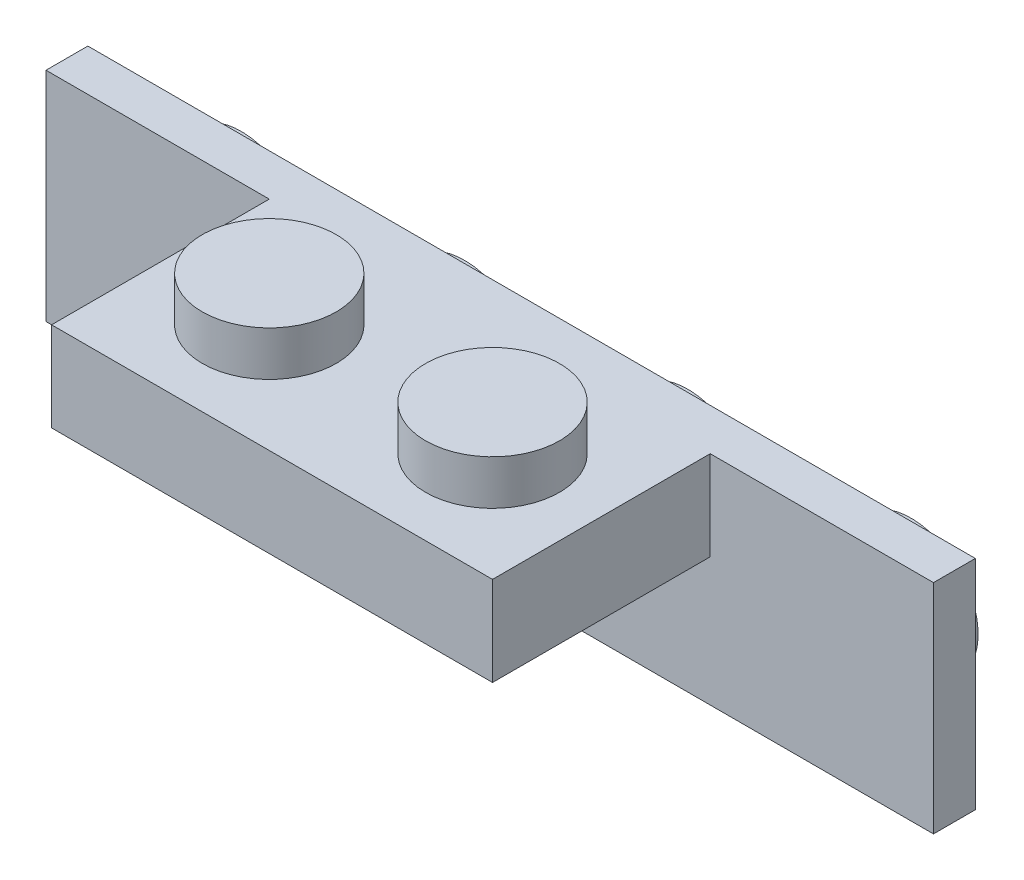
SolidWorks part; units mm, degrees
material "ABS"
ref_plane "Front Plane" through (0, 0, 0) normal (0, 0, 1) x (1, 0, 0)
ref_plane "Top Plane" through (0, 0, 0) normal (0, 1, 0) x (1, 0, 0)
ref_plane "Right Plane" through (0, 0, 0) normal (1, 0, 0) x (0, 0, -1)
sketch "Sketch1" plane through (0, 0, 0) normal (0, 0, 1) x (1, 0, 0)
  line L1 (0, 0) -> (15.8, 0)
  line L2 (0, 0) -> (0, 3.2)
  line L3 (0, 3.2) -> (15.8, 3.2)
  line L4 (15.8, 0) -> (15.8, 3.2)
  dimension "D1" = 3.2
  dimension "D2" = 15.8
extrude "Boss-Extrude1" add sketch "Sketch1" against normal blind 7.8
sketch "Sketch2" plane through (0, 3.2, 0) normal (0, 1, 0) x (1, 0, 0)
  line L0 (0, 7.8) -> (0, 0) construction
  line L1 (15.8, 0) -> (0, 0) construction
  circle A0 centre (3.9, 3.9) radius 2.4
  dimension "D1" = 4.8
  dimension "D2" = 3.9
  dimension "D3" = 3.9
extrude "Boss-Extrude2" add sketch "Sketch2" along normal blind 1.6 contours A0
pattern_linear "LPattern1" count 2 spacing 8 along (0, 0, 1) count 6 spacing 8 along (1, 0, 0) of "Boss-Extrude2"
shell "Shell1" thickness 1.2
sketch "Sketch3" plane through (0, 2, 0) normal (0, -1, 0) x (1, 0, 0)
  line L0 (0, 0) -> (15.8, 0) construction
  line L1 (15.8, -7.8) -> (15.8, 0) construction
  circle A0 centre (7.9, -3.9) radius 1.5
  circle A1 centre (7.9, -3.9) radius 0.6
  dimension "D1" = 3
  dimension "D2" = 1.2
  dimension "D3" = 3.9
  dimension "D4" = 7.9
extrude "Boss-Extrude3" add sketch "Sketch3" along normal offset from surface (1.8 mm away) 0.2 up to face at (7.9, 0, -3.9)
sketch "Sketch4" plane through (0, 0, -7.8) normal (0, 0, -1) x (-1, 0, 0)
  line L0 (-15.8, 3.2) -> (-23.8, 3.2)
  line L1 (-23.8, 3.2) -> (-23.8, -4.6)
  line L2 (-23.8, -4.6) -> (8, -4.6)
  line L3 (8, -4.6) -> (8, 3.2)
  line L4 (8, 3.2) -> (0, 3.2)
  line L5 (0, 3.2) -> (-15.8, 3.2)
  dimension "D1" = 8
  dimension "D2" = 8
  dimension "D3" = 7.8
extrude "Boss-Extrude4" add sketch "Sketch4" along normal blind 1.5
sketch "Sketch5" plane through (0, 0, -9.3) normal (0, 0, -1) x (-1, 0, 0)
  line L0 (8, -4.6) -> (8, 3.2) construction
  line L1 (-23.8, -4.6) -> (8, -4.6) construction
  circle A0 centre (4.1, -0.7) radius 2.4
  circle A1 centre (4.1, -0.7) radius 1.55
  dimension "D1" = 4.8
  dimension "D4" = 0.85
  dimension "D2" = 3.9
  dimension "D3" = 3.9
extrude "Boss-Extrude5" add sketch "Sketch5" along normal blind 1.6
pattern_linear "LPattern2" count 4 spacing 8 along (1, 0, 0) of "Boss-Extrude5"
